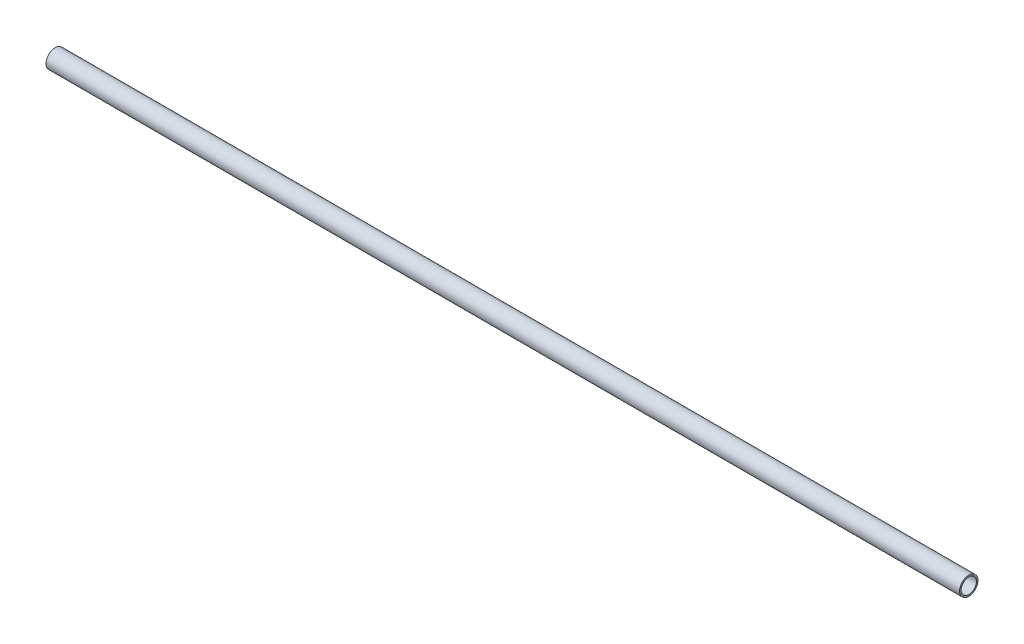
SolidWorks part; units mm, degrees
material "ABS"
ref_plane "Front Plane" through (0, 0, 0) normal (0, 0, 1) x (1, 0, 0)
ref_plane "Top Plane" through (0, 0, 0) normal (0, 1, 0) x (1, 0, 0)
ref_plane "Right Plane" through (0, 0, 0) normal (1, 0, 0) x (0, 0, -1)
sketch "Sketch1" plane through (0, 0, 0) normal (1, 0, 0) x (0, 0, -1)
  circle A0 centre (0, 0) radius 19.05
  circle A1 centre (0, 0) radius 15.875
  dimension "D1" = 38.1
  dimension "D2" = 3.175
extrude "Boss-Extrude1" add sketch "Sketch1" along normal blind 1892.3
